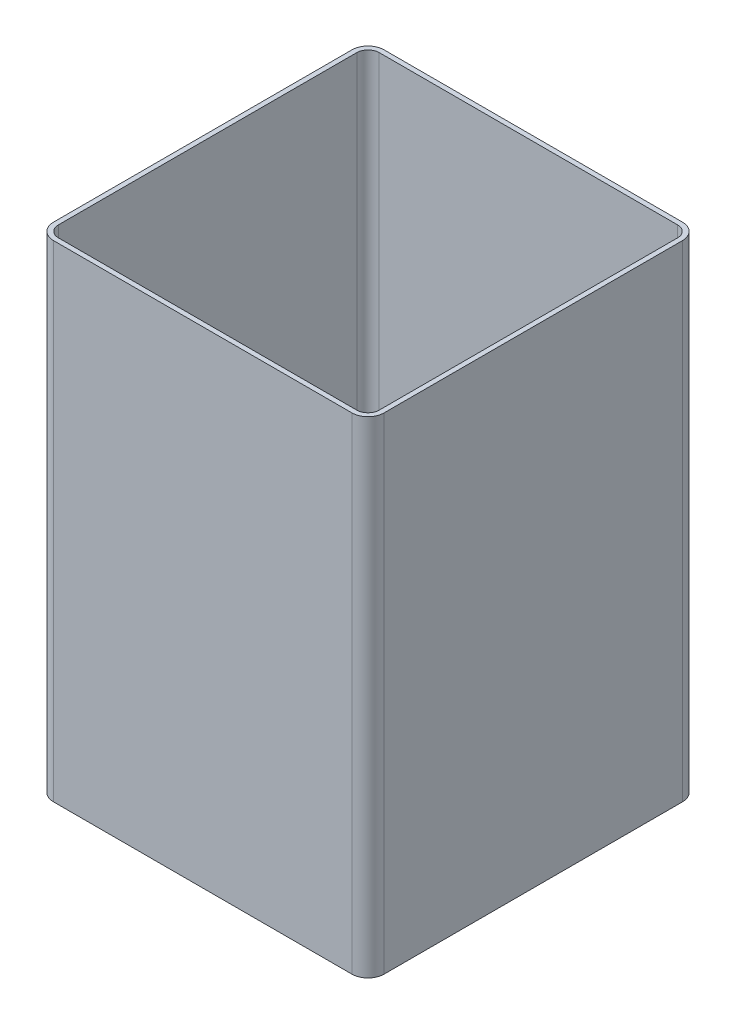
SolidWorks part; units mm, degrees
ref_plane "Front Plane" through (0, 0, 0) normal (0, 0, 1) x (1, 0, 0)
ref_plane "Top Plane" through (0, 0, 0) normal (0, 1, 0) x (1, 0, 0)
ref_plane "Right Plane" through (0, 0, 0) normal (1, 0, 0) x (0, 0, -1)
sketch "Sketch1" plane through (0, 0, 0) normal (0, 1, 0) x (1, 0, 0)
  line L1 (-103, -103) -> (103, -103)
  line L2 (-103, -103) -> (-103, 103)
  line L3 (-103, 103) -> (103, 103)
  line L4 (103, -103) -> (103, 103)
  line L5 (-103, -103) -> (103, 103) construction
  line L6 (-103, 103) -> (103, -103) construction
  point P0 (0, 0)
  dimension "D1" = 206
  dimension "D2" = 206
extrude "Boss-Extrude1" add sketch "Sketch1" along normal blind 303
fillet "Fillet1" radius 10 4 edges at (-103, 151.5, -103) (103, 151.5, -103) (-103, 151.5, 103) (103, 151.5, 103)
shell "Shell1" thickness 3
